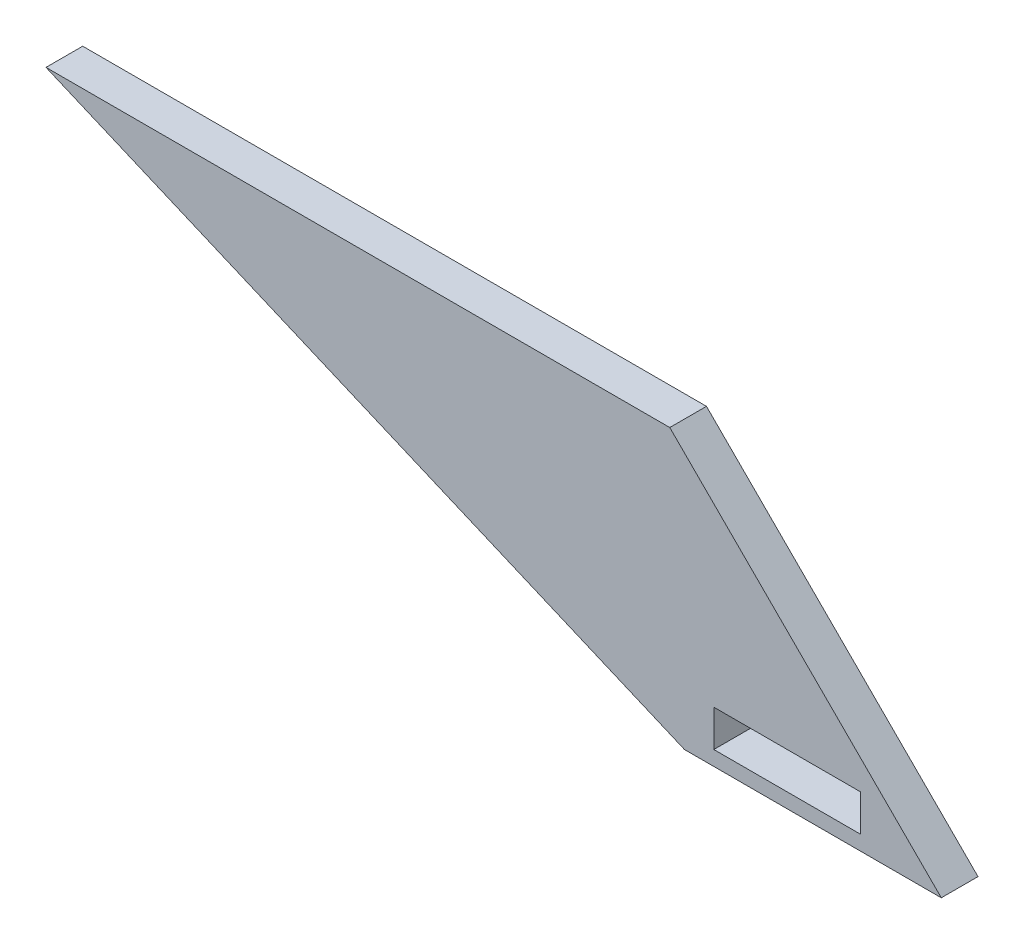
SolidWorks part; units mm, degrees
ref_plane "Front Plane" through (0, 0, 0) normal (0, 0, 1) x (1, 0, 0)
ref_plane "Top Plane" through (0, 0, 0) normal (0, 1, 0) x (1, 0, 0)
ref_plane "Right Plane" through (0, 0, 0) normal (1, 0, 0) x (0, 0, -1)
sketch "Sketch2" plane through (0, 0, 0) normal (0, 0, 1) x (1, 0, 0)
  line L0 (-72.0825, 43.5967) -> (12.9175, 43.5967)
  line L1 (12.9175, 43.5967) -> (49.9175, 6.5967)
  line L2 (14.9175, 6.5967) -> (-72.0825, 43.5967)
  line L4 (49.9175, 6.5967) -> (14.9175, 6.5967)
  dimension "D1" = 35
  dimension "D2" = 135
  dimension "D3" = 85
  dimension "D4" = 37
extrude "Boss-Extrude2" add sketch "Sketch2" along normal blind 5
sketch "Sketch3" plane through (0, 0, 5) normal (0, 0, 1) x (1, 0, 0)
  line L1 (18.9175, 13.5967) -> (38.9175, 13.5967)
  line L2 (18.9175, 13.5967) -> (18.9175, 8.5967)
  line L3 (18.9175, 8.5967) -> (38.9175, 8.5967)
  line L4 (38.9175, 13.5967) -> (38.9175, 8.5967)
  line L5 (18.9175, 13.5967) -> (38.9175, 8.5967) construction
  line L6 (18.9175, 8.5967) -> (38.9175, 13.5967) construction
  line L7 (14.9175, 6.5967) -> (49.9175, 6.5967) construction
  point P0 (28.9175, 11.0967)
  point P7 (0, 0)
  dimension "D1" = 20
  dimension "D2" = 5
  dimension "D3" = 4
  dimension "D4" = 2
extrude "Cut-Extrude1" cut sketch "Sketch3" against normal blind 10
